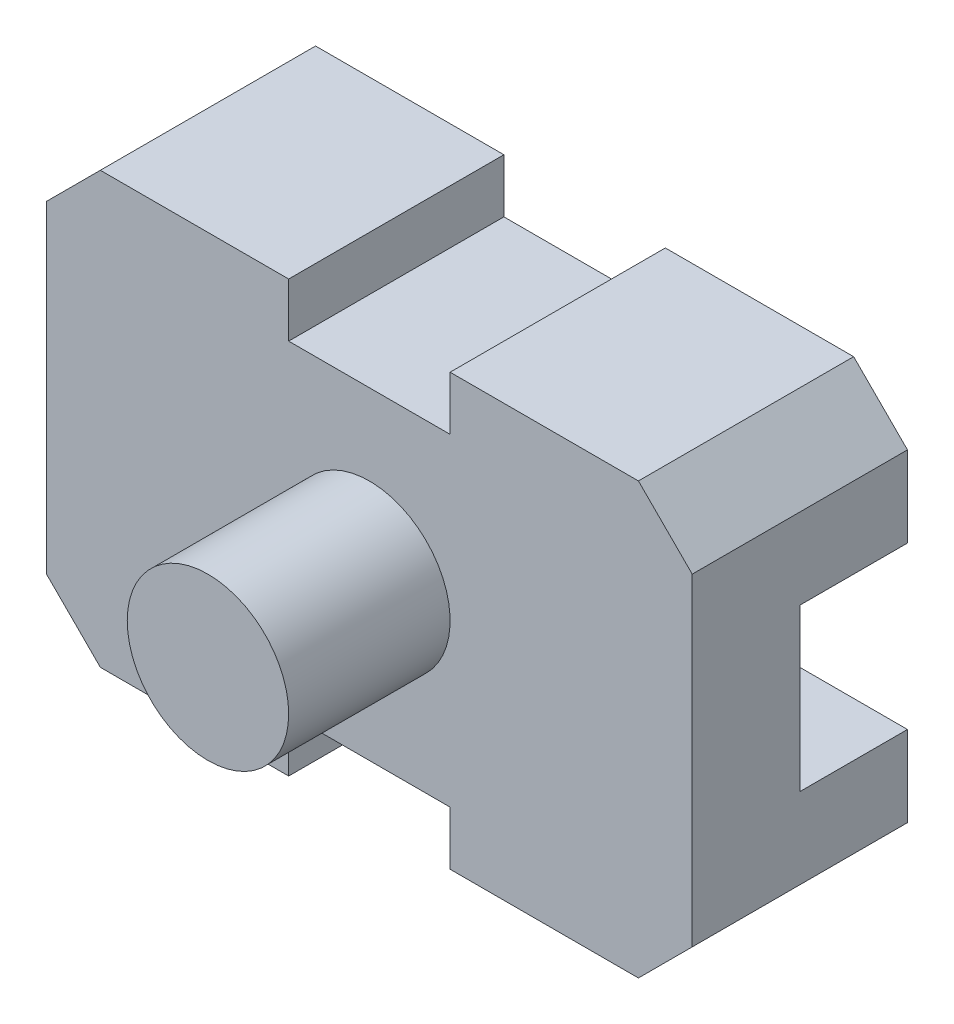
SolidWorks part; units mm, degrees
material "Сталь"
ref_plane "Спереди" through (0, 0, 0) normal (0, 0, 1) x (1, 0, 0)
ref_plane "Сверху" through (0, 0, 0) normal (0, 1, 0) x (1, 0, 0)
ref_plane "Справа" through (0, 0, 0) normal (1, 0, 0) x (0, 0, -1)
sketch "Эскиз1" plane through (0, 0, 0) normal (0, 0, 1) x (1, 0, 0)
  line L1 (-30, -20) -> (30, -20)
  line L2 (-30, -20) -> (-30, 20)
  line L3 (-30, 20) -> (30, 20)
  line L4 (30, -20) -> (30, 20)
  line L5 (-30, -20) -> (30, 20) construction
  line L6 (-30, 20) -> (30, -20) construction
  point P0 (0, 0)
  dimension "D1" = 40
  dimension "D2" = 60
extrude "Бобышка-Вытянуть1" add sketch "Эскиз1" along normal blind 20
sketch "Эскиз2" plane through (0, 0, 20) normal (0, 0, 1) x (1, 0, 0)
  circle A0 centre (0, 0) radius 7.5
  dimension "D1" = 15
extrude "Бобышка-Вытянуть2" add sketch "Эскиз2" along normal blind 15
sketch "Эскиз3" plane through (0, 0, 20) normal (0, 0, 1) x (1, 0, 0)
  line L0 (0, 20) -> (0, -20) construction
  line L1 (30, 20) -> (-30, 20) construction
  line L2 (-30, -20) -> (30, -20) construction
  line L4 (-7.5, -15) -> (7.5, -15)
  line L5 (-7.5, -15) -> (-7.5, -20)
  line L6 (-7.5, -20) -> (7.5, -20)
  line L7 (7.5, -15) -> (7.5, -20)
  line L8 (-7.5, -15) -> (7.5, -20) construction
  line L9 (-7.5, -20) -> (7.5, -15) construction
  point P6 (0, -17.5)
  dimension "D1" = 15
  dimension "D2" = 5
extrude "Вырез-Вытянуть1" cut sketch "Эскиз3" against normal through all
mirror "Зеркальное отражение1" about plane through (0, 0, 0) normal (0, 1, 0) of "Вырез-Вытянуть1"
sketch "Эскиз4" plane through (-30, 0, 0) normal (-1, 0, 0) x (0, 0, 1)
  line L0 (0, 0) -> (20, 0) construction
  line L1 (0, 20) -> (0, -20) construction
  line L2 (20, 20) -> (20, -20) construction
  line L4 (10, -7.5) -> (0, -7.5)
  line L5 (10, -7.5) -> (10, 7.5)
  line L6 (10, 7.5) -> (0, 7.5)
  line L7 (0, -7.5) -> (0, 7.5)
  line L8 (10, -7.5) -> (0, 7.5) construction
  line L9 (10, 7.5) -> (0, -7.5) construction
  point P6 (5, 0)
  dimension "D1" = 15
  dimension "D2" = 10
extrude "Вырез-Вытянуть2" cut sketch "Эскиз4" against normal through all
chamfer "Фаска1" distance 5 angle 45 4 edges at (30, -20, 10) (30, 20, 10) (-30, 20, 10) (-30, -20, 10)
